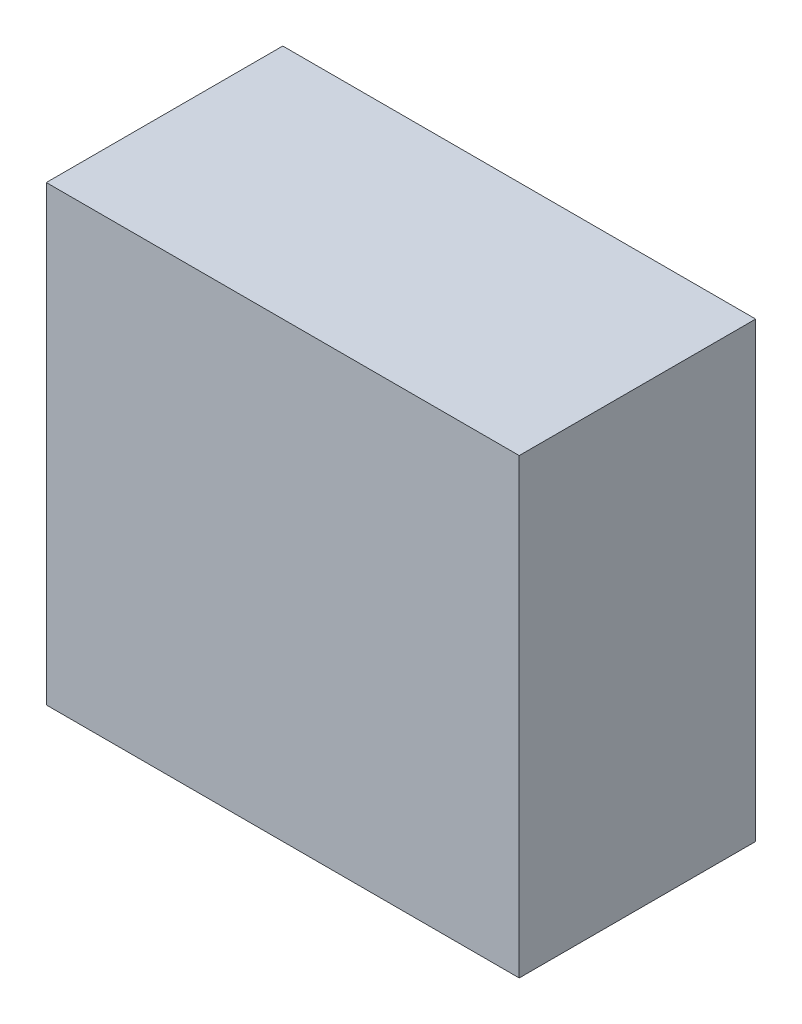
SolidWorks part; units mm, degrees
ref_plane "Front Plane" through (0, 0, 0) normal (0, 0, 1) x (1, 0, 0)
ref_plane "Top Plane" through (0, 0, 0) normal (0, 1, 0) x (1, 0, 0)
ref_plane "Right Plane" through (0, 0, 0) normal (1, 0, 0) x (0, 0, -1)
sketch "Sketch1" plane through (0, 0, 0) normal (0, 0, 1) x (1, 0, 0)
  line L1 (-25.4, 24.3013) -> (25.4, 24.3013)
  line L2 (-25.4, 24.3013) -> (-25.4, -24.3013)
  line L3 (-25.4, -24.3013) -> (25.4, -24.3013)
  line L4 (25.4, 24.3013) -> (25.4, -24.3013)
  line L5 (-25.4, 24.3013) -> (25.4, -24.3013) construction
  line L6 (-25.4, -24.3013) -> (25.4, 24.3013) construction
  point P0 (0, 0)
  point P6 (24.9956, 24.3013)
extrude "Boss-Extrude1" add sketch "Sketch1" along normal blind 25.4
